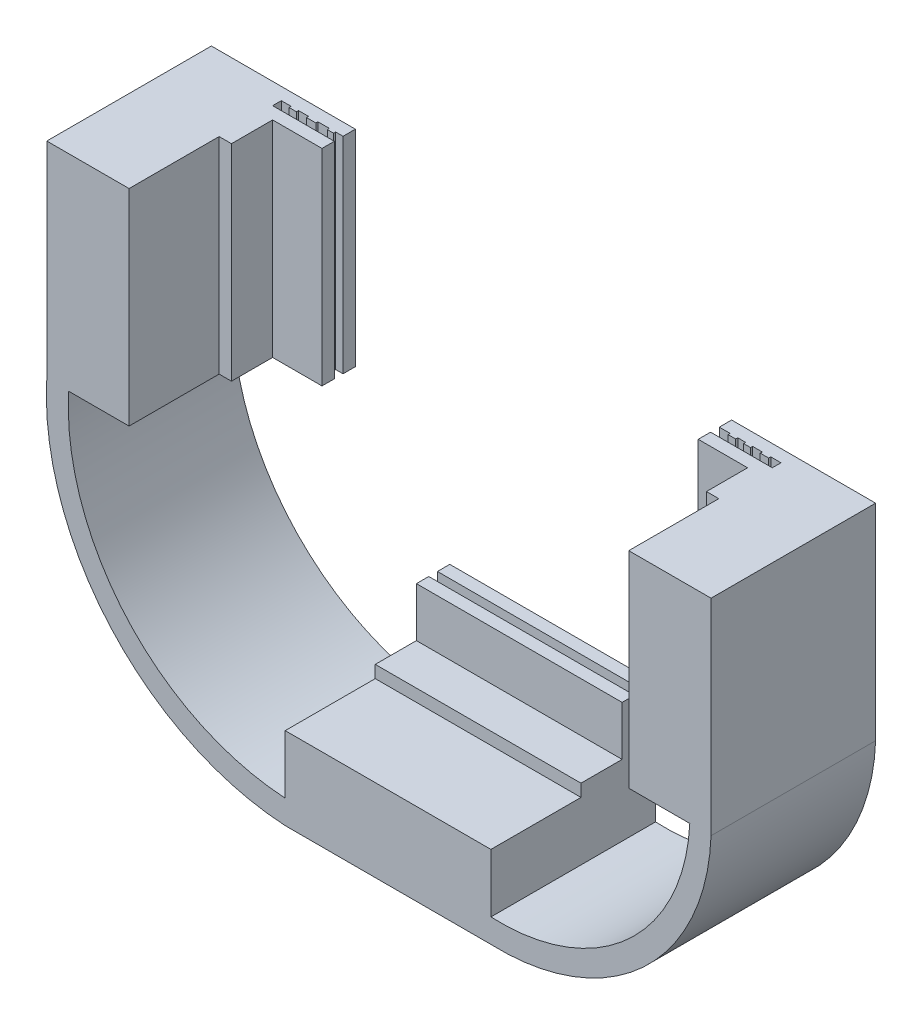
SolidWorks part; units mm, degrees
material "Custom Plastic"
ref_plane "X-Y Datum" through (0, 0, 0) normal (0, 0, 1) x (1, 0, 0)
ref_plane "X-Z Datum" through (0, 0, 0) normal (0, 1, 0) x (1, 0, 0)
ref_plane "Y-Z Datum" through (0, 0, 0) normal (1, 0, 0) x (0, 0, -1)
sketch "Sketch1" plane through (0, 0, 0) normal (0, 0, 1) x (1, 0, 0)
  line L1 (0, 0) -> (12.7, 0)
  line L2 (0, 0) -> (0, 5.08)
  line L3 (0, 5.08) -> (12.7, 5.08)
  line L4 (12.7, 0) -> (12.7, 5.08)
extrude "Boss-Extrude1" add sketch "Sketch1" along normal blind 10.16
sketch "Sketch2" plane through (0, 5.08, 0) normal (0, 1, 0) x (1, 0, 0)
  line L0 (12.7, -10.16) -> (12.7, 0) construction
  line L1 (0, 0) -> (12.7, 0)
  line L2 (0, 0) -> (0, -0.762)
  line L3 (0, -0.762) -> (12.7, -0.762)
  line L4 (12.7, 0) -> (12.7, -0.762)
extrude "Boss-Extrude3" add sketch "Sketch2" along normal blind 3.81
sketch "Sketch4" plane through (0, 5.08, 0) normal (0, 1, 0) x (1, 0, 0)
  line L3 (0, -10.16) -> (0, -0.762) construction
  line L4 (1.196, -2.061) -> (0, -2.061)
  line L6 (1.196, -1.299) -> (0, -1.299)
  line L7 (0, -2.061) -> (0, -1.299)
  line L8 (12.7, -10.16) -> (12.7, -0.762) construction
  line L9 (1.196, -1.299) -> (12.7, -1.299)
  line L11 (1.196, -2.061) -> (12.7, -2.061)
  line L12 (12.7, -1.299) -> (12.7, -2.061)
  dimension "D1" = 0.762
extrude "Boss-Extrude4" add sketch "Sketch4" along normal blind 3.81
move or copy body "Body-Move/Copy1" bodies to move or copy 104 copy yes number of copies 1 translate (-19.746, 19.1694, 0)
move or copy body "Body-Move/Copy3" bodies to move or copy 106 copy no rotation origin (-13.396, 25.7659, 0) rotation axis (0, 0, -1) rotation angle 90
move or copy body "Body-Move/Copy5" bodies to move or copy 108 copy yes number of copies 1 translate (40.5077, -2.2302, 0)
move or copy body "Body-Move/Copy6" bodies to move or copy 110 copy no rotation origin (27.1117, 25.7659, 0) rotation axis (0, 0, 1) rotation angle 180
move or copy body "Body-Move/Copy7" bodies to move or copy 111 copy no translate (-7.4197, -9.0403, 0)
move or copy body "Body-Move/Copy8" bodies to move or copy 108 copy no translate (5.2747, -2.8733, 0)
sketch "Sketch12" plane through (0, 0, 10.16) normal (0, 0, 1) x (1, 0, 0)
  line L0 (0, 5.08) -> (0, 0) construction
  line L1 (-14.7178, 16.5426) -> (-9.6378, 16.5426) construction
  line L2 (12.7, 0) -> (12.7, 5.08) construction
  line L3 (21.2085, 12.6058) -> (26.2885, 12.6058) construction
  line L4 (-14.7178, 16.5426) -> (-13.3646, 16.5426)
  line L5 (0, 1.469) -> (0, 0)
  line L6 (12.7, 1.469) -> (12.7, 0)
  line L7 (24.9758, 12.6058) -> (26.2885, 12.6058)
  arc A0 (0, 0) -> (-14.7178, 16.5426) centre (0.9124, 15.6302) cw
  arc A1 (26.2885, 12.6058) -> (12.7, 0) centre (13.1914, 13.0971) cw
  arc A2 (0, 1.469) -> (-13.3646, 16.5426) centre (0.8545, 15.6881) cw
  arc A3 (12.7, 1.469) -> (24.9758, 12.6058) centre (13.2695, 13.1753) ccw
extrude "Boss-Extrude6" add sketch "Sketch12" against normal blind 10.16
sketch "Sketch17" plane through (0, 0, 0.762) normal (0, 0, 1) x (1, 0, 0)
  line L0 (12.7, 8.89) -> (12.7, 5.08) construction
  line L1 (12.7, 8.3005) -> (0, 8.3005)
  line L2 (12.7, 8.3005) -> (12.7, 7.7135)
  line L3 (12.7, 7.7135) -> (0, 7.7135)
  line L4 (0, 8.3005) -> (0, 7.7135)
  line L5 (0, 8.89) -> (0, 5.08) construction
  line L6 (-5.8278, 16.5426) -> (-9.6378, 16.5426) construction
  line L7 (12.7, 7.1972) -> (0, 7.1972)
  line L8 (12.7, 7.1972) -> (12.7, 6.637)
  line L9 (12.7, 6.637) -> (0, 6.637)
  line L10 (0, 7.1972) -> (0, 6.637)
  line L11 (12.7, 6.1167) -> (0, 6.1167)
  line L12 (12.7, 6.1167) -> (12.7, 5.6463)
  line L13 (12.7, 5.6463) -> (0, 5.6463)
  line L14 (0, 6.1167) -> (0, 5.6463)
  line L15 (-6.6735, 16.5426) -> (-6.2845, 16.5426)
  line L16 (-6.6735, 16.5426) -> (-6.6735, 29.2426)
  line L17 (-6.6735, 29.2426) -> (-6.2845, 29.2426)
  line L18 (-6.2845, 16.5426) -> (-6.2845, 29.2426)
  line L19 (-5.8278, 29.2426) -> (-9.6378, 29.2426) construction
  line L20 (17.3985, 25.3058) -> (21.2085, 25.3058) construction
  line L21 (-7.3834, 16.5426) -> (-7.9498, 16.5426)
  line L22 (-7.3834, 16.5426) -> (-7.3834, 29.2426)
  line L23 (-7.3834, 29.2426) -> (-7.9498, 29.2426)
  line L24 (-7.9498, 16.5426) -> (-7.9498, 29.2426)
  line L25 (-9.0379, 29.2426) -> (-8.5772, 29.2426)
  line L26 (-9.0379, 29.2426) -> (-9.0379, 16.5426)
  line L27 (-9.0379, 16.5426) -> (-8.5772, 16.5426)
  line L28 (-8.5772, 29.2426) -> (-8.5772, 16.5426)
  line L29 (20.5767, 25.3058) -> (20.0539, 25.3058)
  line L30 (20.5767, 25.3058) -> (20.5767, 12.6058)
  line L31 (20.5767, 12.6058) -> (20.0539, 12.6058)
  line L32 (20.0539, 25.3058) -> (20.0539, 12.6058)
  line L33 (17.3985, 12.6058) -> (21.2085, 12.6058) construction
  line L35 (19.4504, 25.3058) -> (19.0321, 25.3058)
  line L36 (19.4504, 25.3058) -> (19.4504, 12.6058)
  line L37 (19.4504, 12.6058) -> (19.0321, 12.6058)
  line L38 (19.0321, 25.3058) -> (19.0321, 12.6058)
  line L39 (18.5411, 25.3058) -> (18.0748, 25.3058)
  line L40 (18.5411, 25.3058) -> (18.5411, 12.6121)
  line L41 (18.5411, 12.6121) -> (18.0748, 12.6121)
  line L42 (18.0748, 25.3058) -> (18.0748, 12.6121)
extrude "Boss-Extrude10" add sketch "Sketch17" along normal blind 0.127
sketch "Sketch18" plane through (0, 0, 2.061) normal (0, 0, 1) x (1, 0, 0)
  line L0 (-5.8278, 29.2426) -> (-9.6378, 29.2426) construction
  line L1 (-8.8758, 29.2426) -> (-9.6378, 29.2426)
  line L2 (-8.8758, 29.2426) -> (-8.8758, 16.5426)
  line L3 (-8.8758, 16.5426) -> (-9.6378, 16.5426)
  line L4 (-9.6378, 29.2426) -> (-9.6378, 16.5426)
  line L5 (12.7, 8.89) -> (12.7, 5.08) construction
  line L6 (0, 5.08) -> (12.7, 5.08)
  line L7 (0, 5.08) -> (0, 5.842)
  line L8 (0, 5.842) -> (12.7, 5.842)
  line L9 (12.7, 5.08) -> (12.7, 5.842)
  line L10 (17.3985, 25.3058) -> (21.2085, 25.3058) construction
  line L11 (21.2085, 12.6058) -> (20.4465, 12.6058)
  line L12 (21.2085, 12.6058) -> (21.2085, 25.3058)
  line L13 (21.2085, 25.3058) -> (20.4465, 25.3058)
  line L14 (20.4465, 12.6058) -> (20.4465, 25.3058)
extrude "Boss-Extrude11" add sketch "Sketch18" along normal blind 2.54
